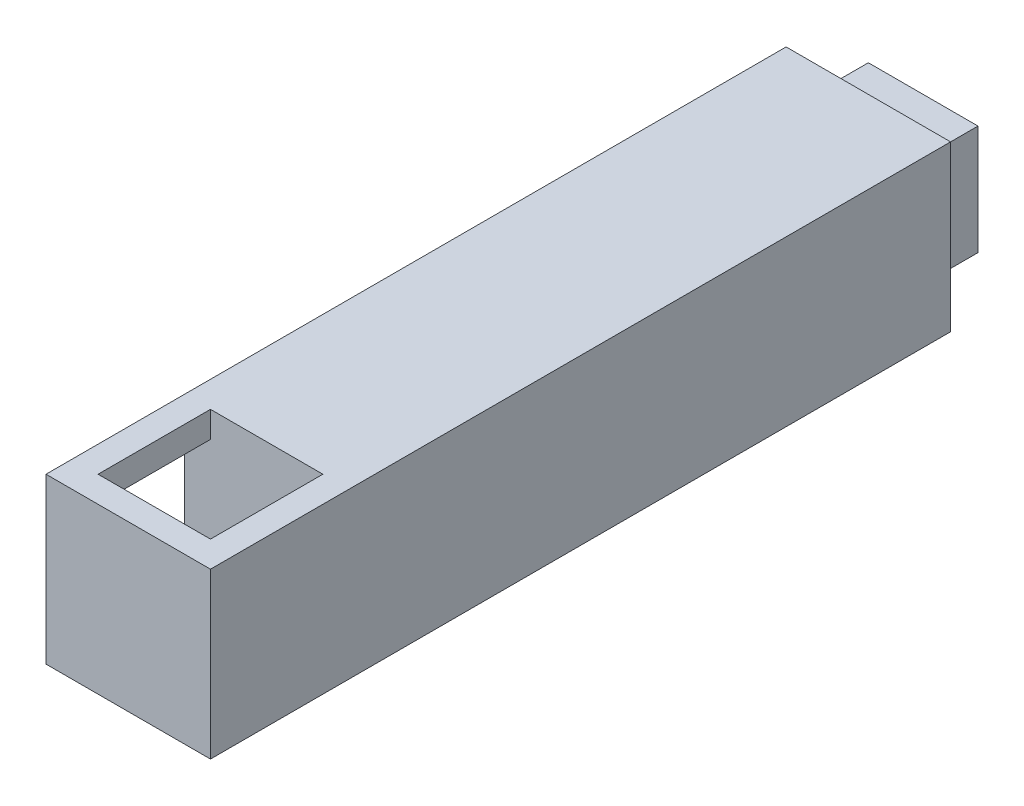
SolidWorks part; units mm, degrees
ref_plane "Front Plane" through (0, 0, 0) normal (0, 0, 1) x (1, 0, 0)
ref_plane "Top Plane" through (0, 0, 0) normal (0, 1, 0) x (1, 0, 0)
ref_plane "Right Plane" through (0, 0, 0) normal (1, 0, 0) x (0, 0, -1)
sketch "Sketch1" plane through (0, 0, 0) normal (0, 0, 1) x (1, 0, 0)
  line L1 (-15, -15) -> (15, -15)
  line L2 (-15, -15) -> (-15, 15)
  line L3 (-15, 15) -> (15, 15)
  line L4 (15, -15) -> (15, 15)
extrude "Boss-Extrude1" add sketch "Sketch1" along normal blind 135
sketch "Sketch2" plane through (0, 0, 0) normal (0, 0, 1) x (1, 0, 0)
  line L1 (-10, -10) -> (10, -10)
  line L2 (-10, -10) -> (-10, 10)
  line L3 (-10, 10) -> (10, 10)
  line L4 (10, -10) -> (10, 10)
extrude "Boss-Extrude2" add sketch "Sketch2" against normal blind 10
sketch "Sketch3" plane through (-15, 0, 0) normal (-1, 0, 0) x (0, 0, 1)
  line L0 (109.75, -10.25) -> (130.25, -10.25)
  line L1 (130.25, -10.25) -> (130.25, 10.25)
  line L2 (130.25, 10.25) -> (109.75, 10.25)
  line L3 (109.75, 10.25) -> (109.75, -10.25)
extrude "Cut-Extrude2" cut sketch "Sketch3" against normal blind 15
sketch "Sketch4" plane through (0, 15, 0) normal (0, 1, 0) x (1, 0, 0)
  line L0 (-10.25, -130.25) -> (10.25, -130.25)
  line L1 (10.25, -130.25) -> (10.25, -109.75)
  line L2 (10.25, -109.75) -> (-10.25, -109.75)
  line L3 (-10.25, -109.75) -> (-10.25, -130.25)
extrude "Cut-Extrude3" cut sketch "Sketch4" against normal blind 15
